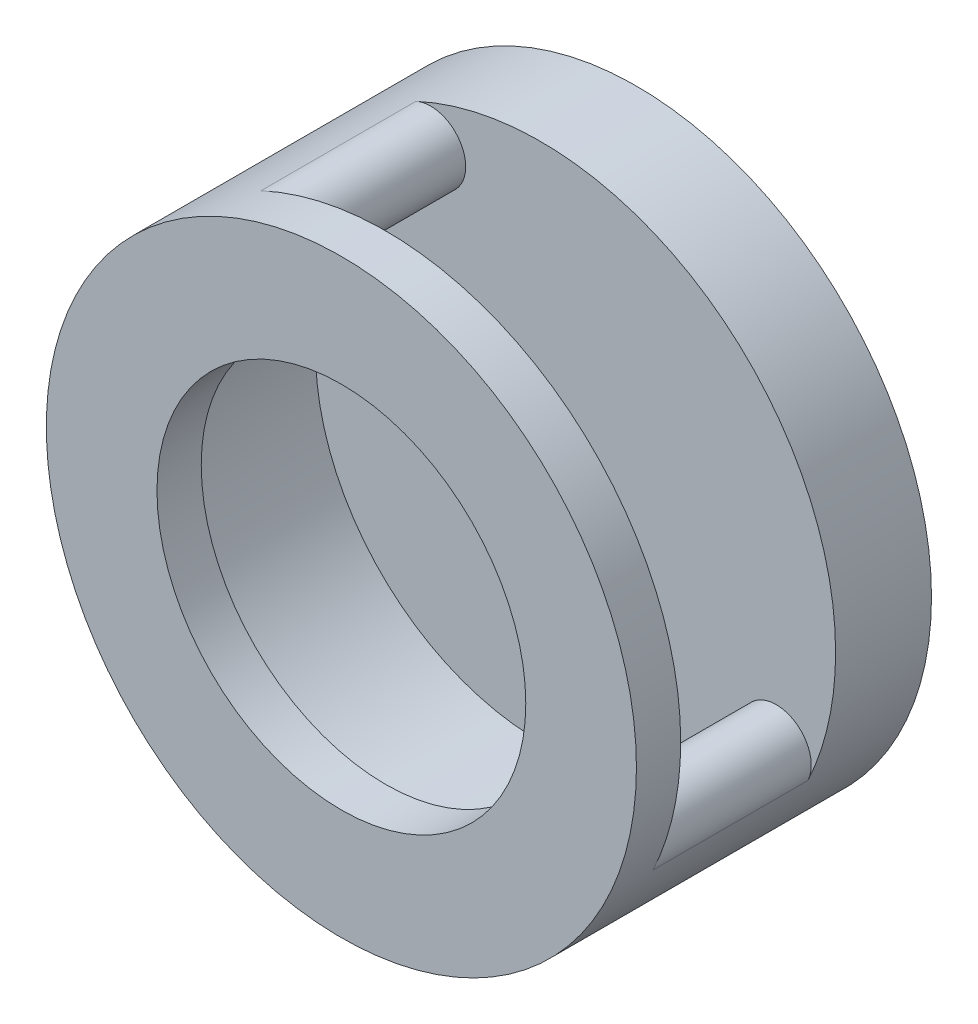
SolidWorks part; units mm, degrees
ref_plane "前视基准面" through (0, 0, 0) normal (0, 0, 1) x (1, 0, 0)
ref_plane "上视基准面" through (0, 0, 0) normal (0, 1, 0) x (1, 0, 0)
ref_plane "右视基准面" through (0, 0, 0) normal (1, 0, 0) x (0, 0, -1)
sketch "草图1" plane through (0, 0, 0) normal (0, 0, 1) x (1, 0, 0)
  circle A0 centre (0, 0) radius 4
  dimension "D1" = 8
extrude "凸台-拉伸1" add sketch "草图1" along normal blind 4
sketch "草图2" plane through (0, 0, 4) normal (0, 0, 1) x (1, 0, 0)
  circle A0 centre (0, 0) radius 2.5
  dimension "D1" = 5
extrude "切除-拉伸1" cut sketch "草图2" against normal blind 0.6
sketch "草图3" plane through (0, 0, 3.4) normal (0, 0, 1) x (1, 0, 0)
  line L0 (0, 0) -> (2.8225, 2.8225) construction
  line L1 (0, 0) -> (1.2811, 0) construction
  line L2 (-1.4897, 3.1947) -> (0, 0) construction
  line L3 (-1.6905, 3.6252) -> (-2.1131, 4.5315)
  line L4 (3.6252, -1.6905) -> (4.5315, -2.1131)
  arc A0 (-1.289, 2.7642) -> (2.7642, -1.289) centre (0, 0) ccw
  arc A1 (-1.289, 2.7642) -> (-1.6905, 3.6252) centre (-1.4897, 3.1947) ccw
  arc A5 (2.7642, -1.289) -> (3.6252, -1.6905) centre (3.1947, -1.4897) cw
  circle A6 centre (0, 0) radius 4
  circle A7 centre (0, 0) radius 4 construction
  arc A8 (4.5315, -2.1131) -> (-2.1131, 4.5315) centre (0, 0) ccw
  dimension "D1" = 6.1
  dimension "D3" = 0
  dimension "D5" = 10
  dimension "D2" = 45
  dimension "D4" = 70
extrude "切除-拉伸2" cut sketch "草图3" against normal blind 2.1
